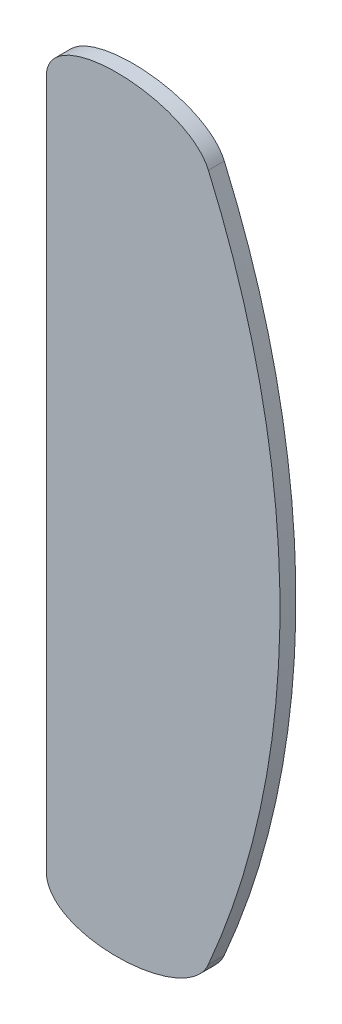
SolidWorks part; units mm, degrees
ref_plane "Front Plane" through (0, 0, 0) normal (0, 0, 1) x (1, 0, 0)
ref_plane "Top Plane" through (0, 0, 0) normal (0, 1, 0) x (1, 0, 0)
ref_plane "Right Plane" through (0, 0, 0) normal (1, 0, 0) x (0, 0, -1)
sketch "Sketch1" plane through (0, 0, 0) normal (0, 0, 1) x (1, 0, 0)
  line L0 (3345.3317, 2756.6021) -> (3345.3317, 1933.2309)
  arc A0 (3539.1282, 1933.2309) -> (3539.3444, 2756.6021) centre (2593.7166, 2345.1647) ccw
  spline S0 degree 3 poles (3539.1282, 1933.2309) (3513.3244, 1874.0095) (3345.3317, 1868.6321) (3345.3317, 1933.2309) knots 0 0 0 0 7.629784 7.629784 7.629784 7.629784
  spline S1 degree 3 poles (3539.3444, 2756.6021) (3513.5429, 2815.9031) (3345.3317, 2821.273) (3345.3317, 2756.6021) knots 0 0 0 0 7.638295 7.638295 7.638295 7.638295
extrude "Boss-Extrude1" add sketch "Sketch1" along normal blind 19.05
